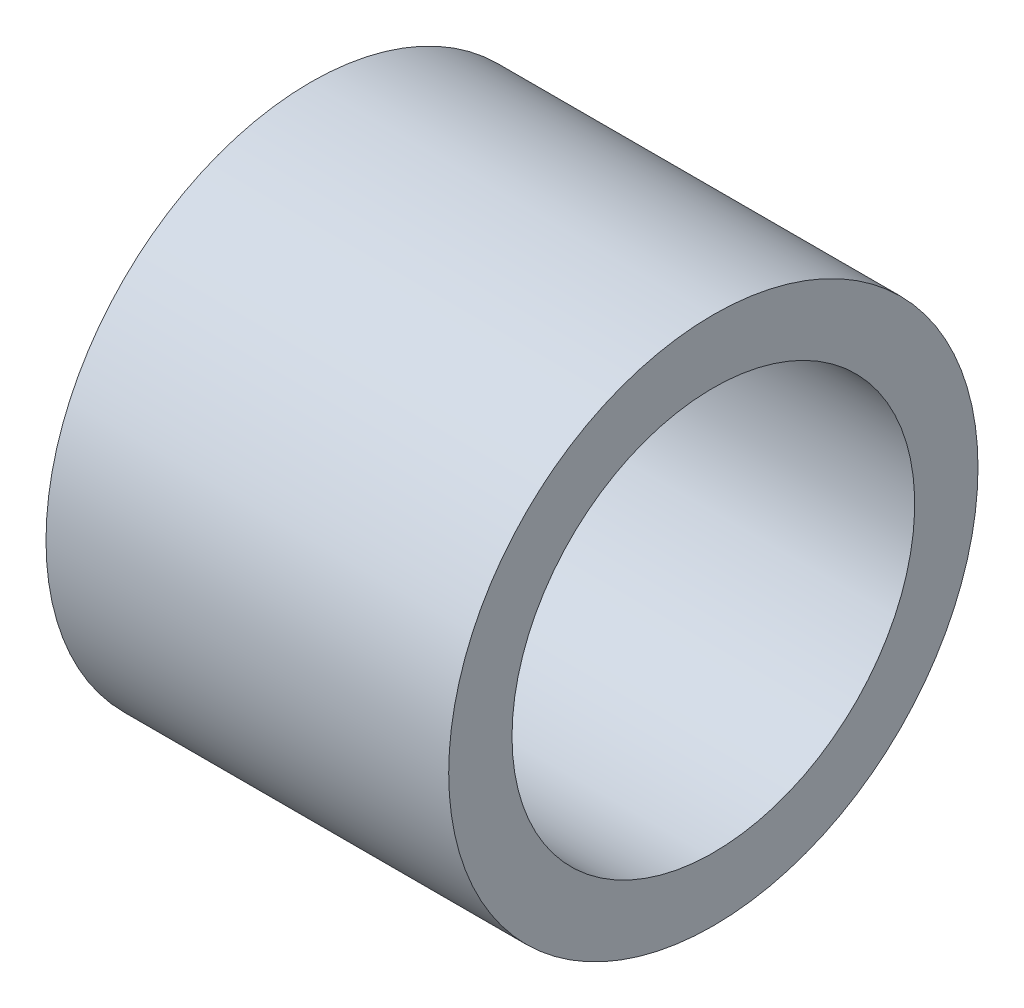
SolidWorks part; units mm, degrees
ref_plane "Front Plane" through (0, 0, 0) normal (0, 0, 1) x (1, 0, 0)
ref_plane "Top Plane" through (0, 0, 0) normal (0, 1, 0) x (1, 0, 0)
ref_plane "Right Plane" through (0, 0, 0) normal (1, 0, 0) x (0, 0, -1)
sketch "Sketch1" plane through (0, 0, 0) normal (1, 0, 0) x (0, 0, -1)
  circle A0 centre (0, 0) radius 9.525
  circle A1 centre (0, 0) radius 12.52
  dimension "D1" = 19.05
  dimension "D2" = 25.04
extrude "Boss-Extrude1" add sketch "Sketch1" along normal mid plane 19.05
